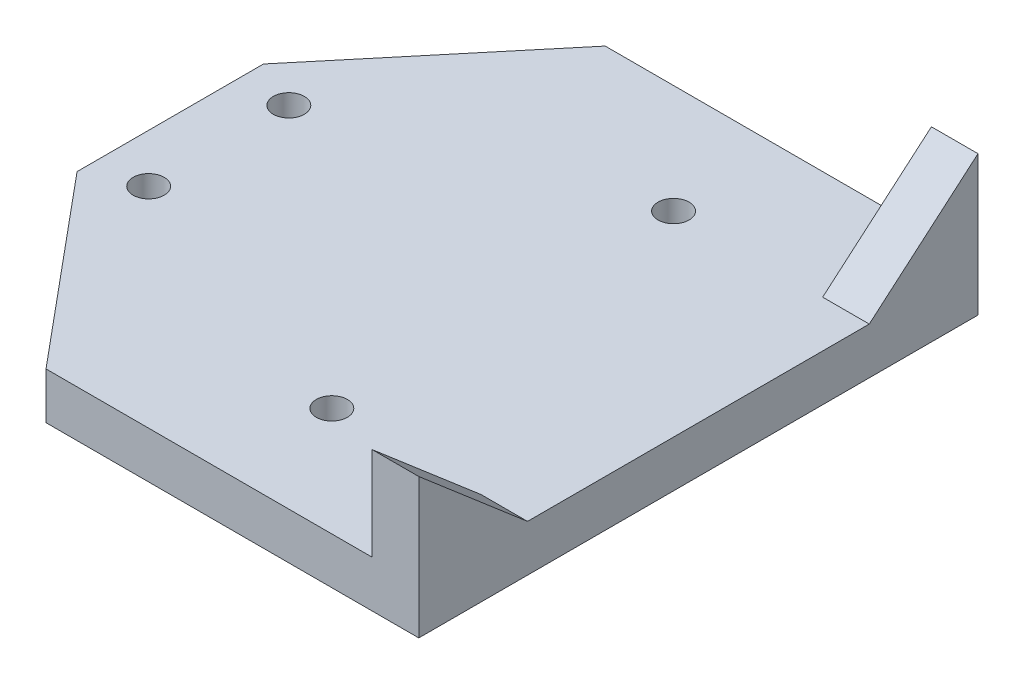
SolidWorks part; units mm, degrees
material "Oak"
ref_plane "Front" through (0, 0, 0) normal (0, 0, 1) x (1, 0, 0)
ref_plane "Top" through (0, 0, 0) normal (0, 1, 0) x (1, 0, 0)
ref_plane "Right" through (0, 0, 0) normal (1, 0, 0) x (0, 0, -1)
sketch "Sketch2" plane through (0, 0, 0) normal (0, 1, 0) x (1, 0, 0)
  line L0 (-99.8257, 0) -> (96.2886, 0) construction
  line L1 (-220, 30) -> (-220, -30)
  line L2 (-220, -30) -> (-170, -90)
  line L3 (-170, -90) -> (-50, -90)
  line L4 (-50, 90) -> (-50, -90)
  line L6 (-170, 90) -> (-50, 90)
  line L7 (-220, 30) -> (-170, 90)
  point P12 (-220, 0)
  dimension "D3" = 50
  dimension "D1" = 30
  dimension "D2" = 220
  dimension "D5" = 120
  dimension "D6" = 90
extrude "Boss-Extrude1" add sketch "Sketch2" along normal blind 15
hole_wizard "Ø1.0mm Dowel Hole1" positions "Sketch4" profile "Sketch3" hole size "Ø1.0" standard "ANSI Metric" end condition through all
sketch "Sketch4" plane through (0, 15, 0) normal (0, 1, 0) x (1, 0, 0)
  line L0 (-27.032, 0) -> (49.1627, 0) construction
  point P30 (-204.3892, 22.5574)
  point P32 (-204.3892, -22.5574)
  point P37 (-112.9963, 55)
  point P39 (-112.9963, -55)
  point P40 (-204.3892, 22.5574)
  dimension "D1" = 110
sketch "Sketch3" plane through (-204.3892, 15, -22.5574) normal (1, 0, 0) x (0, 0, 1)
  line L0 (0, 0) -> (0, 15)
  line L1 (0, 15) -> (5, 15)
  line L2 (5, 15) -> (5, 0)
  line L5 (5, 0) -> (0, 0)
  line L11 (0, -6.35) -> (0, 107.95) construction
  dimension "Thru Hole Dia." = 10
  dimension "Thru Hole Depth" = 15
sketch "Sketch5" plane through (-50, 0, 0) normal (1, 0, 0) x (0, 0, -1)
  line L0 (-90, 15) -> (90, 15) construction
  line L1 (-90, 15) -> (-55, 15)
  line L2 (-90, 15) -> (-90, 45)
  line L3 (-90, 45) -> (-55, 15)
  line L4 (90, 45) -> (90, 15)
  line L5 (90, 45) -> (55, 15)
  line L6 (55, 15) -> (90, 15)
  dimension "D1" = 35
  dimension "D2" = 30
  dimension "D3" = 35
  dimension "D4" = 30
extrude "Boss-Extrude2" add sketch "Sketch5" against normal blind 15
scale "Escala1" scale about centroid uniform scaling yes scale factor 0.2
